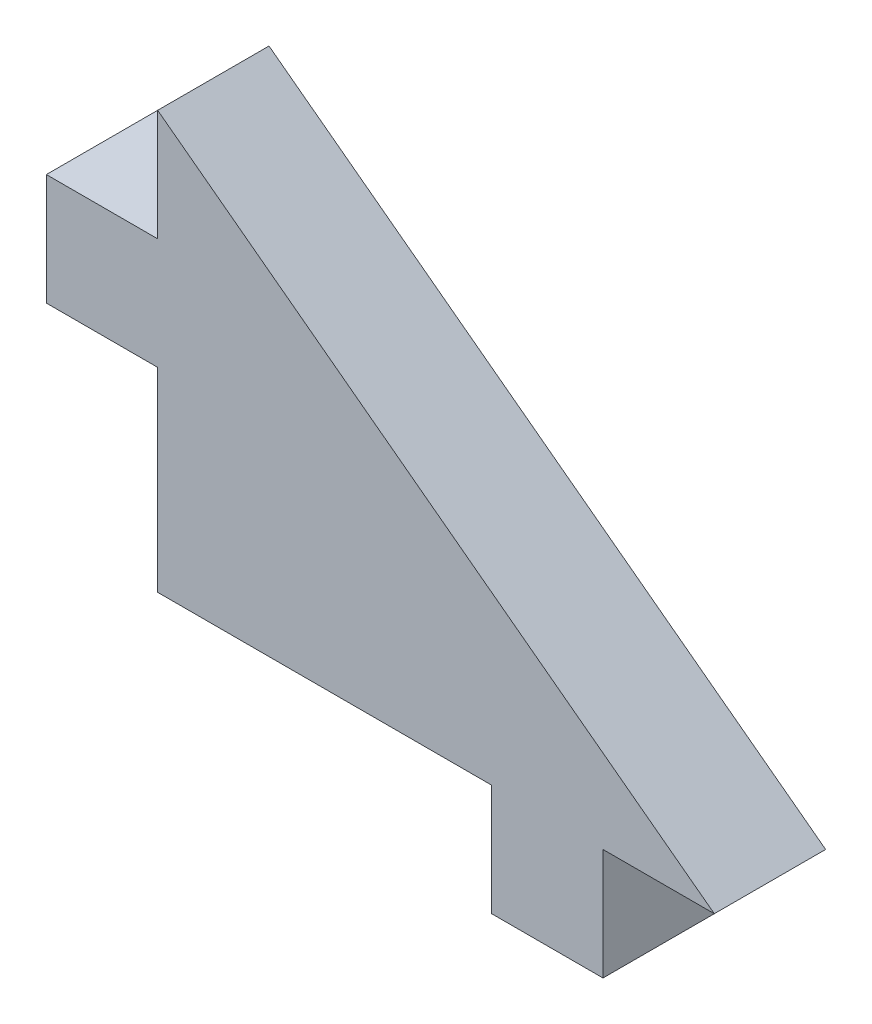
SolidWorks part; units mm, degrees
material "Acrylic (Medium-high impact)"
ref_plane "Front Plane" through (0, 0, 0) normal (0, 0, 1) x (1, 0, 0)
ref_plane "Top Plane" through (0, 0, 0) normal (0, 1, 0) x (1, 0, 0)
ref_plane "Right Plane" through (0, 0, 0) normal (1, 0, 0) x (0, 0, -1)
sketch "Sketch1" plane through (0, 0, 0) normal (0, 0, 1) x (1, 0, 0)
  line L0 (0, 0) -> (0, 30)
  line L1 (0, 0) -> (40, 0)
  line L2 (0, 30) -> (40, 0)
  dimension "D1" = 40
  dimension "D2" = 30
extrude "Side Boss-Extrude1" add sketch "Sketch1" along normal blind 8
sketch "Sketch2" plane through (0, 0, 0) normal (-1, 0, 0) x (0, 0, 1)
  line L0 (0, 30) -> (0, 0) construction
  line L1 (0, 22) -> (8, 22)
  line L2 (0, 22) -> (0, 14)
  line L3 (0, 14) -> (8, 14)
  line L4 (8, 22) -> (8, 14)
  line L5 (8, 30) -> (8, 0) construction
  line L6 (8, 30) -> (0, 30) construction
  dimension "D1" = 8
extrude "Puzzle Slot Back Boss-Extrude2" add sketch "Sketch2" along normal blind 8
sketch "Sketch3" plane through (0, 0, 0) normal (0, -1, 0) x (1, 0, 0)
  line L0 (0, 8) -> (40, 8) construction
  line L1 (32, 8) -> (24, 8)
  line L2 (32, 8) -> (32, 0)
  line L3 (32, 0) -> (24, 0)
  line L4 (24, 8) -> (24, 0)
  line L5 (0, 0) -> (40, 0) construction
  line L6 (40, 8) -> (40, 0) construction
  dimension "D1" = 8
extrude "Puzzle Slot Bottom Boss-Extrude3" add sketch "Sketch3" along normal blind 8
